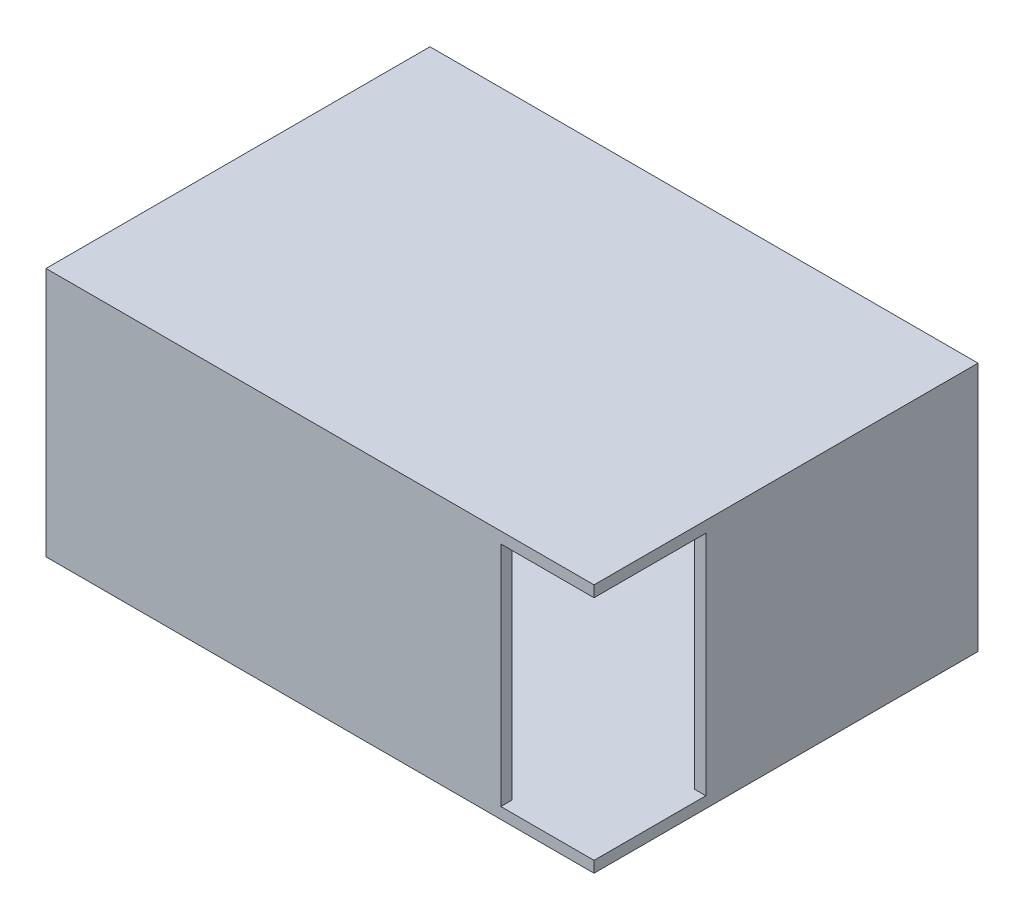
SolidWorks part; units mm, degrees
ref_plane "Front Plane" through (0, 0, 0) normal (1, 0, 0) x (0, 1, 0)
ref_plane "Top Plane" through (0, 0, 0) normal (0, 0, 1) x (0, 1, 0)
ref_plane "Right Plane" through (0, 0, 0) normal (0, 1, 0) x (-1, 0, 0)
sketch "Sketch1" plane through (0, 0, 0) normal (1, 0, 0) x (0, 1, 0)
  line L1 (0, 0) -> (85.09, 0)
  line L2 (0, 0) -> (0, 130.81)
  line L3 (0, 130.81) -> (85.09, 130.81)
  line L4 (85.09, 0) -> (85.09, 130.81)
  dimension "D1" = 130.81
  dimension "D2" = 85.09
extrude "Boss-Extrude1" add sketch "Sketch1" along normal blind 186.69
sketch "Sketch3" plane through (186.69, 0, 0) normal (1, 0, 0) x (0, 1, 0)
  line L0 (3.81, 130.81) -> (81.28, 130.81)
  line L1 (85.09, 130.81) -> (0, 130.81) construction
  line L2 (3.81, 92.71) -> (81.28, 92.71)
  line L3 (3.81, 130.81) -> (3.81, 92.71)
  line L4 (81.28, 130.81) -> (81.28, 92.71)
  line L7 (85.09, 0) -> (85.09, 130.81) construction
  line L8 (0, 130.81) -> (0, 0) construction
  dimension "D1" = 38.1
  dimension "D2" = 3.81
  dimension "D3" = 3.81
extrude "Cut-Extrude3" cut sketch "Sketch3" against normal blind 31.75
sketch "Sketch4" plane through (0, 0, 0) normal (0, 0, -1) x (1, 0, 0)
  line L0 (186.69, 0) -> (0, 0) construction
  line L1 (3.81, -81.28) -> (182.88, -81.28)
  line L2 (3.81, -81.28) -> (3.81, -3.81)
  line L3 (3.81, -3.81) -> (182.88, -3.81)
  line L4 (182.88, -81.28) -> (182.88, -3.81)
  line L5 (0, 0) -> (0, -85.09) construction
  line L6 (186.69, -85.09) -> (0, -85.09) construction
  line L8 (186.69, 0) -> (186.69, -85.09) construction
  dimension "D1" = 3.81
  dimension "D2" = 3.81
  dimension "D3" = 3.81
  dimension "D4" = 3.81
extrude "Cut-Extrude4" cut sketch "Sketch4" against normal blind 127
